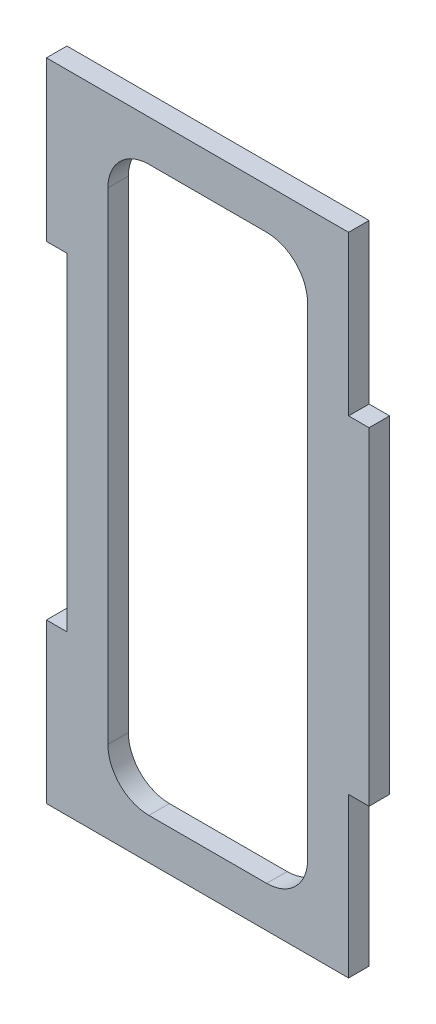
SolidWorks part; units mm, degrees
material "Acrylic (Medium-high impact)"
ref_plane "Front Plane" through (0, 0, 0) normal (0, 0, 1) x (1, 0, 0)
ref_plane "Top Plane" through (0, 0, 0) normal (0, 1, 0) x (1, 0, 0)
ref_plane "Right Plane" through (0, 0, 0) normal (1, 0, 0) x (0, 0, -1)
sketch "Sketch1" plane through (0, 0, 0) normal (0, 0, 1) x (1, 0, 0)
  line L1 (-50, -150.1518) -> (50, -150.1518)
  line L2 (-50, -150.1518) -> (-50, 50)
  line L3 (-50, 50) -> (50, 50)
  line L4 (50, -150.1518) -> (50, 50)
  dimension "D1" = 100
  dimension "D2" = 50
  dimension "D3" = 200.1518
  dimension "D4" = 50
extrude "Boss-Extrude1" add sketch "Sketch1" along normal blind 6.35
sketch "Sketch2" plane through (0, 0, 6.35) normal (0, 0, 1) x (1, 0, 0)
  line L0 (-43.65, 50) -> (-43.65, -150.1518) construction
  line L1 (50, 50) -> (-50, 50) construction
  line L2 (-50, -150.1518) -> (50, -150.1518) construction
  line L3 (-50, -50.0759) -> (50, -50.0759) construction
  line L4 (-50, 50) -> (-50, -150.1518) construction
  line L5 (50, -150.1518) -> (50, 50) construction
  line L6 (43.65, 50) -> (43.65, -150.1518) construction
  line L7 (-43.65, -50.0759) -> (-43.65, 50) construction
  line L8 (43.65, -50.0759) -> (43.65, 50) construction
  line L10 (-50, -50.0759) -> (-43.65, -50.0759)
  line L11 (-50, -50.0759) -> (-50, 0.7241)
  line L12 (-50, 0.7241) -> (-43.65, 0.7241)
  line L13 (-43.65, -50.0759) -> (-43.65, 0.7241)
  line L14 (-50, -50.0759) -> (-43.65, -50.0759)
  line L15 (-50, -50.0759) -> (-50, -100.8759)
  line L16 (-50, -100.8759) -> (-43.65, -100.8759)
  line L17 (-43.65, -50.0759) -> (-43.65, -100.8759)
  line L18 (43.65, 50) -> (50, 50)
  line L19 (43.65, 50) -> (43.65, 0.7241)
  line L20 (43.65, 0.7241) -> (50, 0.7241)
  line L21 (50, 50) -> (50, 0.7241)
  line L22 (43.65, -150.1518) -> (50, -150.1518)
  line L23 (43.65, -150.1518) -> (43.65, -100.8759)
  line L24 (43.65, -100.8759) -> (50, -100.8759)
  line L25 (50, -150.1518) -> (50, -100.8759)
  line M8 (-50, 50) -> (-50, -150.1518)
  line M9 (-50, -150.1518) -> (50, -150.1518)
  line M10 (50, -150.1518) -> (50, 50)
  line M11 (50, 50) -> (-50, 50)
  dimension "D1" = 6.35
  dimension "D2" = 6.35
  dimension "D3" = 100.0759
  dimension "D4" = 50.8
  dimension "D5" = 50.8
  dimension "D6" = 50.8
  dimension "D7" = 50.8
extrude "Cut-Extrude1" cut sketch "Sketch2" against normal blind 6.35 contours L10 L13 L12 M8 | L17 L10 L16 M8 | L19 L20 M10 M11 | L24 L23 M9 M10
sketch "Sketch3" plane through (0, 0, 6.35) normal (0, 0, 1) x (1, 0, 0)
  line L0 (-43.65, -100.8759) -> (-43.65, 0.7241) construction
  line L1 (-30.95, -137.4518) -> (30.95, -137.4518)
  line L2 (-30.95, -137.4518) -> (-30.95, 37.3)
  line L3 (-30.95, 37.3) -> (30.95, 37.3)
  line L4 (30.95, -137.4518) -> (30.95, 37.3)
  line L5 (43.65, 50) -> (-50, 50) construction
  line L6 (43.65, 50) -> (43.65, 0.7241) construction
  line L7 (-50, -150.1518) -> (43.65, -150.1518) construction
  dimension "D1" = 12.7
  dimension "D2" = 12.7
  dimension "D3" = 12.7
  dimension "D4" = 12.7
extrude "Cut-Extrude2" cut sketch "Sketch3" against normal blind 6.35
fillet "Fillet1" radius 12.7 4 edges at (30.95, -137.4518, 3.175) (30.95, 37.3, 3.175) (-30.95, 37.3, 3.175) (-30.95, -137.4518, 3.175)
